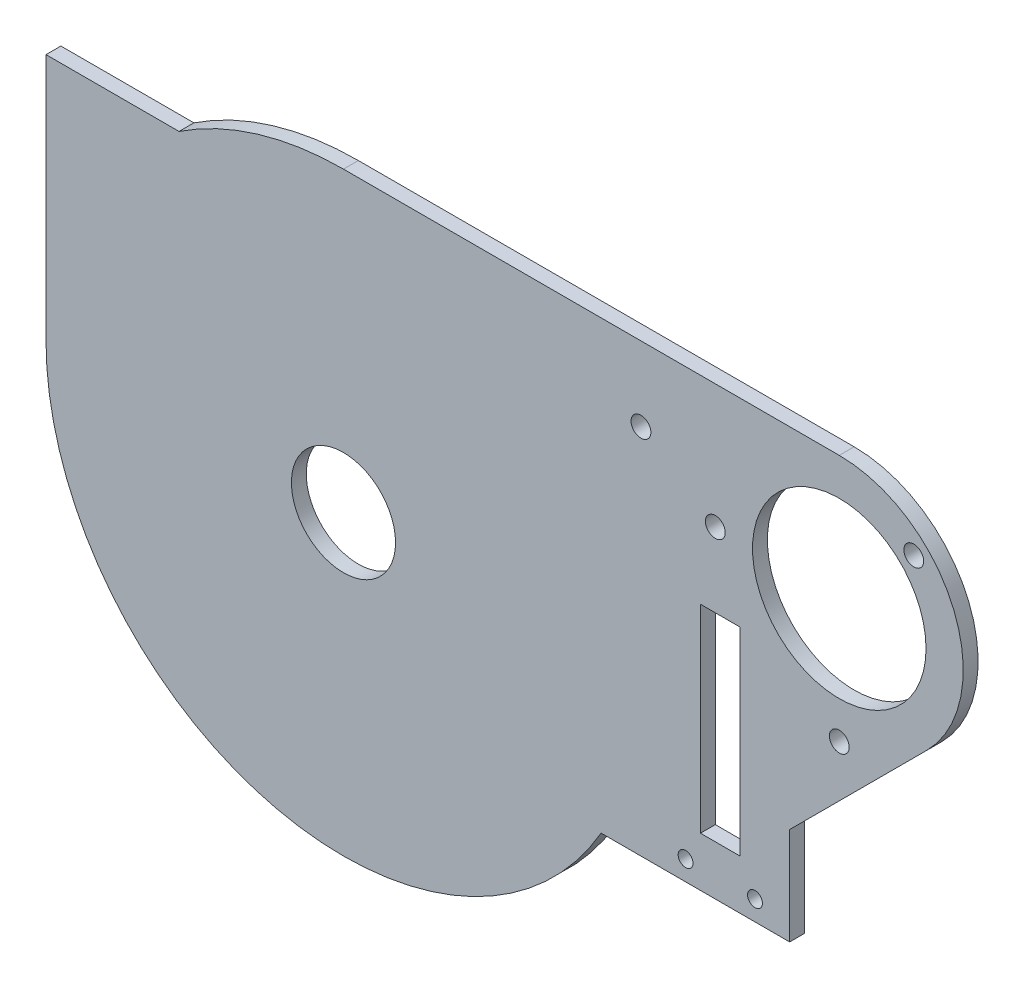
SolidWorks part; units mm, degrees
ref_plane "前视基准面" through (0, 0, 0) normal (0, 0, 1) x (1, 0, 0)
ref_plane "上视基准面" through (0, 0, 0) normal (0, 1, 0) x (1, 0, 0)
ref_plane "右视基准面" through (0, 0, 0) normal (1, 0, 0) x (0, 0, -1)
sketch "Sketch1" plane through (0, 0, 0) normal (0, 0, 1) x (1, 0, 0)
  line L0 (-10.9179, 60) -> (113.3582, 60) construction
  line L3 (-33.1662, 50) -> (-60, 50)
  line L4 (-60, 0) -> (-60, 50)
  line L6 (67.51, -32.8453) -> (81.2655, -19.0899) construction
  line L7 (90, -10.3553) -> (117.6777, 17.3223)
  line L12 (76, 7.9315) -> (76, -17.4174) construction
  line L13 (0, 60) -> (100, 60)
  line L15 (72, 20) -> (80, 20)
  line L16 (72, 20) -> (72, -20)
  line L17 (72, -20) -> (80, -20)
  line L18 (80, 20) -> (80, -20)
  line L19 (72, 20) -> (80, -20) construction
  line L20 (72, -20) -> (80, 20) construction
  line L23 (90, -30) -> (56.5685, -30)
  line L24 (90, -30) -> (90, -10.3553)
  line L25 (56.5685, -30) -> (51.9615, -30)
  line L26 (57.5608, -26) -> (84.9155, -26) construction
  arc A0 (0, 60) -> (51.9615, -30) centre (0, 0) ccw
  circle A2 centre (0, 0) radius 10.5
  arc A8 (117.6777, 17.3223) -> (100, 60) centre (100, 35) ccw
  circle A9 centre (100, 35) radius 17.5
  circle A10 centre (69, -26) radius 1.5
  circle A11 centre (83, -26) radius 1.5
  point P18 (76, 0)
  dimension "D1" = 120
  dimension "D2" = 136
  dimension "D3" = 21
  dimension "D5" = 50
  dimension "D4" = 100
  dimension "D6" = 35
  dimension "D13" = 7
  dimension "D7" = 10
  dimension "D8" = 8
  dimension "D9" = 40
  dimension "D10" = 90
  dimension "D11" = 150
  dimension "D12" = 6
extrude "Boss-Extrude1" add sketch "Sketch1" along normal blind 3
sketch "Sketch2" plane through (0, 0, 3) normal (0, 0, 1) x (1, 0, 0)
  line L1 (-60, 0) -> (-60, 50) construction
  line L2 (0, 60) -> (100, 60) construction
  circle A1 centre (0, 0) radius 57
  circle A2 centre (60, 45) radius 2
  circle A6 centre (100, 35) radius 14
  dimension "D1" = 15
  dimension "D5" = 28
  dimension "D2" = 120
extrude "Cut-Extrude1" cut sketch "Sketch2" against normal up to next
sketch "Sketch3" plane through (0, 0, 3) normal (0, 0, 1) x (1, 0, 0)
  line L0 (117.6777, 52.6777) -> (112.3744, 47.3744) construction
  circle A0 centre (100, 35) radius 17.5 construction
  circle A1 centre (100, 35) radius 25 construction
  circle A2 centre (100, 10) radius 2
  circle A3 centre (75, 35) radius 2
  circle A4 centre (115.026, 50.026) radius 2
  dimension "D1" = 35
extrude "Cut-Extrude2" cut sketch "Sketch3" against normal up to next
